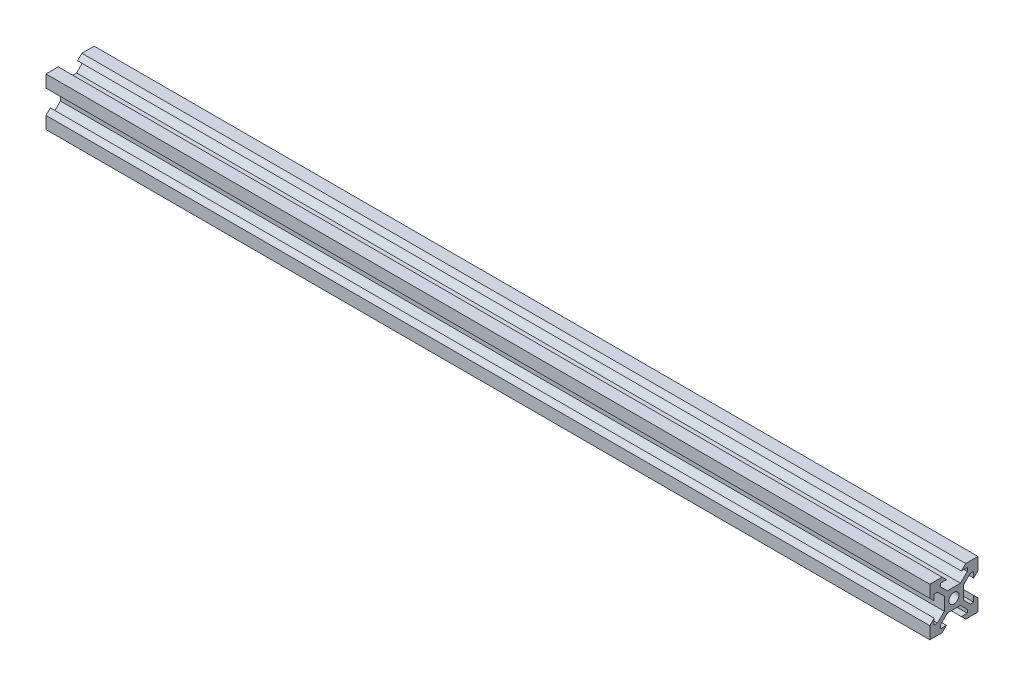
SolidWorks part; units mm, degrees
ref_plane "Front Plane" through (0, 0, 0) normal (0, 0, 1) x (1, 0, 0)
ref_plane "Top Plane" through (0, 0, 0) normal (0, 1, 0) x (1, 0, 0)
ref_plane "Right Plane" through (0, 0, 0) normal (1, 0, 0) x (0, 0, -1)
sketch "Sketch1" plane through (0, 0, 0) normal (1, 0, 0) x (0, 0, -1)
  line L0 (0, 0) -> (0, 20) construction
  line L1 (10, 14) -> (10, 6) construction
  line L2 (5.1, 20) -> (5.1, 0) construction
  line L3 (6.9, 18.2) -> (6.9, 1.8) construction
  line L4 (4.4444, 18.2) -> (4.4444, 1.8) construction
  line L5 (3.1716, 15.5556) -> (3.1716, 4.4444) construction
  line L6 (10, 6) -> (10, 14) construction
  line L7 (6, 12.7272) -> (6, 7.2728)
  line L8 (6, 7.2728) -> (3.1716, 4.4444)
  line L9 (1.8, 4.4444) -> (3.1716, 4.4444)
  line L10 (1.8, 4.4444) -> (1.8, 6.9)
  line L11 (1.8, 6.9) -> (0, 5.1)
  line L12 (0, 5.1) -> (0, 0)
  line L13 (0, 0) -> (5.1, 0)
  line L14 (5.1, 0) -> (6.9, 1.8)
  line L15 (6.9, 1.8) -> (4.4444, 1.8)
  line L16 (4.4444, 3.1716) -> (4.4444, 1.8)
  line L17 (4.4444, 3.1716) -> (7.2728, 6)
  line L18 (7.2728, 6) -> (12.7272, 6)
  line L19 (1.8, 15.5556) -> (1.8, 4.4444) construction
  line L20 (20, 10) -> (0, 10) construction
  line L21 (1.8, 10) -> (0, 10) construction
  line L22 (7.2728, 14) -> (7.2728, 6) construction
  line L23 (6.9, 1.8) -> (0, 1.8) construction
  line L24 (5.8586, 15.4142) -> (5.8586, 4.5858) construction
  line L25 (4.5858, 14.1414) -> (4.5858, 5.8586) construction
  line L26 (10, 10) -> (20, 20) construction
  line L27 (14.1414, 15.4142) -> (15.4142, 14.1414) construction
  line L28 (10, 10) -> (0, 0) construction
  line L29 (14.7778, 14.7778) -> (20, 20) construction
  line L30 (5.8586, 4.5858) -> (4.5858, 5.8586) construction
  line L31 (5.2222, 5.2222) -> (0, 0) construction
  line L32 (14.7778, 5.2222) -> (20, 0) construction
  line L33 (10, 6) -> (10, 14) construction
  line L34 (14.1414, 4.5858) -> (15.4142, 5.8586) construction
  line L35 (10, 10) -> (20, 0) construction
  line L36 (15.4142, 14.1414) -> (15.4142, 5.8586) construction
  line L37 (14.1414, 15.4142) -> (14.1414, 4.5858) construction
  line L38 (13.1, 1.8) -> (20, 1.8) construction
  line L39 (12.7272, 14) -> (12.7272, 6) construction
  line L40 (18.2, 10) -> (20, 10) construction
  line L41 (18.2, 15.5556) -> (18.2, 4.4444) construction
  line L42 (16.8284, 15.5556) -> (16.8284, 4.4444) construction
  line L43 (15.5556, 18.2) -> (15.5556, 1.8) construction
  line L44 (13.1, 18.2) -> (13.1, 1.8) construction
  line L45 (14.9, 20) -> (14.9, 0) construction
  line L46 (20, 0) -> (20, 20) construction
  line L47 (14, 12.7272) -> (16.8284, 15.5556)
  line L48 (18.2, 15.5556) -> (16.8284, 15.5556)
  line L49 (18.2, 15.5556) -> (18.2, 13.1)
  line L50 (18.2, 13.1) -> (20, 14.9)
  line L51 (20, 14.9) -> (20, 20)
  line L52 (20, 20) -> (14.9, 20)
  line L53 (14.9, 20) -> (13.1, 18.2)
  line L54 (13.1, 18.2) -> (15.5556, 18.2)
  line L55 (15.5556, 16.8284) -> (15.5556, 18.2)
  line L56 (15.5556, 16.8284) -> (12.7272, 14)
  line L57 (15.5556, 3.1716) -> (12.7272, 6)
  line L58 (15.5556, 3.1716) -> (15.5556, 1.8)
  line L59 (13.1, 1.8) -> (15.5556, 1.8)
  line L60 (14.9, 0) -> (13.1, 1.8)
  line L61 (20, 0) -> (14.9, 0)
  line L62 (20, 5.1) -> (20, 0)
  line L63 (5.2222, 14.7778) -> (0, 20) construction
  line L64 (5.8586, 15.4142) -> (4.5858, 14.1414) construction
  line L65 (18.2, 6.9) -> (20, 5.1)
  line L66 (10, 10) -> (0, 20) construction
  line L67 (18.2, 4.4444) -> (18.2, 6.9)
  line L68 (18.2, 4.4444) -> (16.8284, 4.4444)
  line L69 (14, 7.2728) -> (16.8284, 4.4444)
  line L70 (14, 12.7272) -> (14, 7.2728)
  line L93 (7.2728, 14) -> (12.7272, 14)
  line L94 (4.4444, 16.8284) -> (7.2728, 14)
  line L95 (4.4444, 16.8284) -> (4.4444, 18.2)
  line L96 (6.9, 18.2) -> (4.4444, 18.2)
  line L97 (5.1, 20) -> (6.9, 18.2)
  line L98 (0, 20) -> (5.1, 20)
  line L99 (0, 14.9) -> (0, 20)
  line L100 (1.8, 13.1) -> (0, 14.9)
  line L101 (1.8, 15.5556) -> (1.8, 13.1)
  line L102 (1.8, 15.5556) -> (3.1716, 15.5556)
  line L103 (6, 12.7272) -> (3.1716, 15.5556)
  circle A0 centre (10, 10) radius 2.1
  point P57 (14, 10)
  point P108 (6, 10)
  dimension "D5" = 4.2
  dimension "D2" = 20
  dimension "D3" = 10
  dimension "D4" = 5.1
  dimension "D6" = 10
  dimension "D7" = 1.8
  dimension "D8" = 1.8
  dimension "D9" = 1.3716
  dimension "D10" = 1.8
  dimension "D11" = 1.8
  dimension "D12" = 4
  dimension "D13" = 1.2728
  dimension "D14" = 5.1
  dimension "D16" = 1.8
  dimension "D18" = 4
extrude "Boss-Extrude1" add sketch "Sketch1" along normal blind 367
